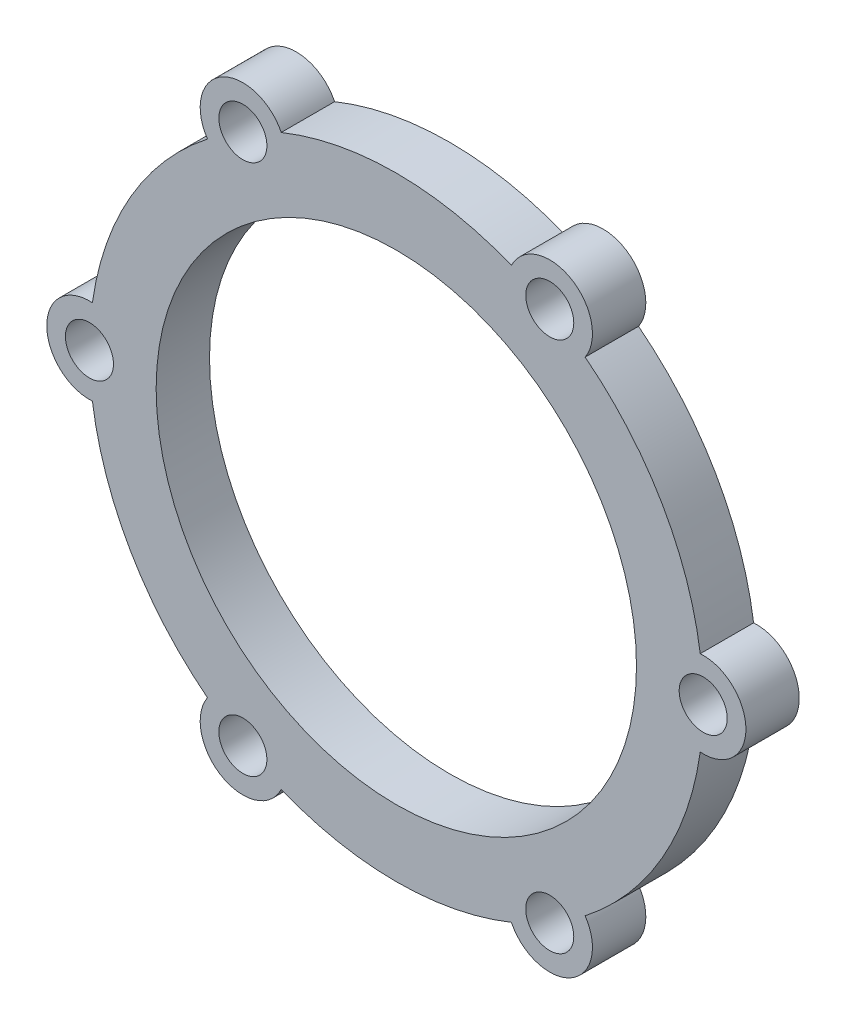
SolidWorks part; units mm, degrees
ref_plane "Front Plane" through (0, 0, 0) normal (1, 0, 0) x (0, 1, 0)
ref_plane "Top Plane" through (0, 0, 0) normal (0, 0, 1) x (0, 1, 0)
ref_plane "Right Plane" through (0, 0, 0) normal (0, 1, 0) x (-1, 0, 0)
sketch "Sketch1" plane through (0, 0, 0) normal (0, 0, 1) x (0, 1, 0)
  circle A0 centre (0, 0) radius 57.5
  dimension "D1" = 115
extrude "Extrude-Thin1" add sketch "Sketch1" along normal mid plane 10 thin contours A0 thin type one direction reverse wall 12.5
sketch "Sketch2" plane through (0, 0, 5) normal (0, 0, 1) x (1, 0, 0)
  circle A0 centre (57.5, 0) radius 8
  circle A1 centre (0, 0) radius 57.5 construction
  point P4 (0, 0)
  dimension "D1" = 16
extrude "Boss-Extrude1" add sketch "Sketch2" against normal up to surface (10 mm away) up to face at (57.5, 0, -5)
sketch "Sketch3" plane through (0, 0, 5) normal (0, 0, 1) x (1, 0, 0)
  circle A0 centre (57.5, 0) radius 4.5
  dimension "D1" = 9
extrude "Cut-Extrude1" cut sketch "Sketch3" against normal through all both and the other way through all
pattern_circular "CirPattern1" count 6 over 360 about axis through (0, 0, 0) along (0, 0, 1) of "Boss-Extrude1", "Cut-Extrude1"
